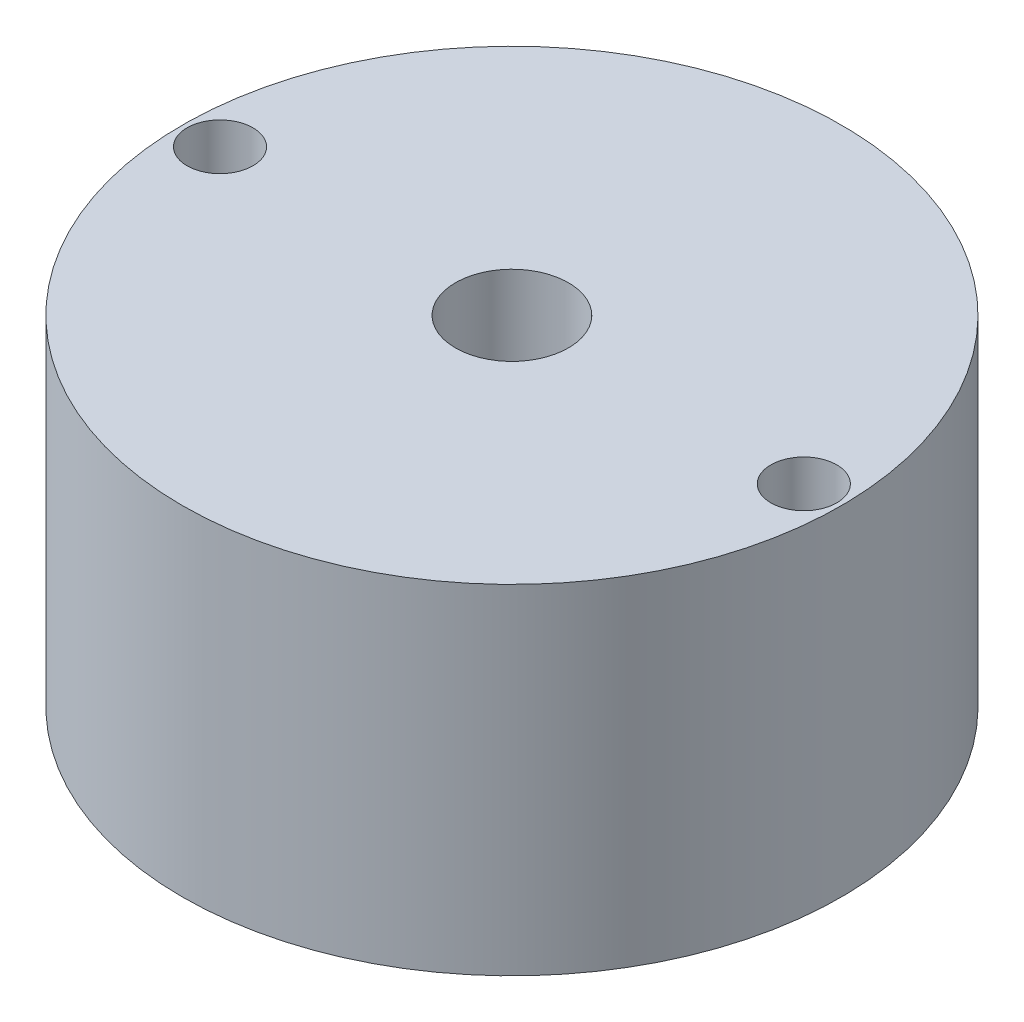
SolidWorks part; units mm, degrees
ref_plane "前视基准面" through (0, 0, 0) normal (0, 0, 1) x (1, 0, 0)
ref_plane "上视基准面" through (0, 0, 0) normal (0, 1, 0) x (1, 0, 0)
ref_plane "右视基准面" through (0, 0, 0) normal (1, 0, 0) x (0, 0, -1)
other "Configuration Table"
sketch "草图1" plane through (0, 0, 0) normal (0, 1, 0) x (1, 0, 0)
  circle A0 centre (0, 0) radius 17.5
  dimension "D1" = 35
extrude "凸台-拉伸1" add sketch "草图1" along normal blind 18
sketch "草图2" plane through (0, 18, 0) normal (0, 1, 0) x (1, 0, 0)
  circle A0 centre (0, 0) radius 3
  dimension "D1" = 6
extrude "切除-拉伸1" cut sketch "草图2" against normal blind 12
sketch "草图3" plane through (0, 18, 0) normal (0, 1, 0) x (1, 0, 0)
  circle A0 centre (15.5, 0) radius 1.75
  circle A1 centre (-15.5, 0) radius 1.75
  point P4 (0, 0)
  point P5 (0, 0)
  point P7 (16.0537, -4.1058)
  point P8 (0, 0)
  dimension "D1" = 3.5
  dimension "D2" = 3.5
  dimension "D3" = 31
  dimension "D4" = 15.5
extrude "切除-拉伸2" cut sketch "草图3" against normal blind 8
